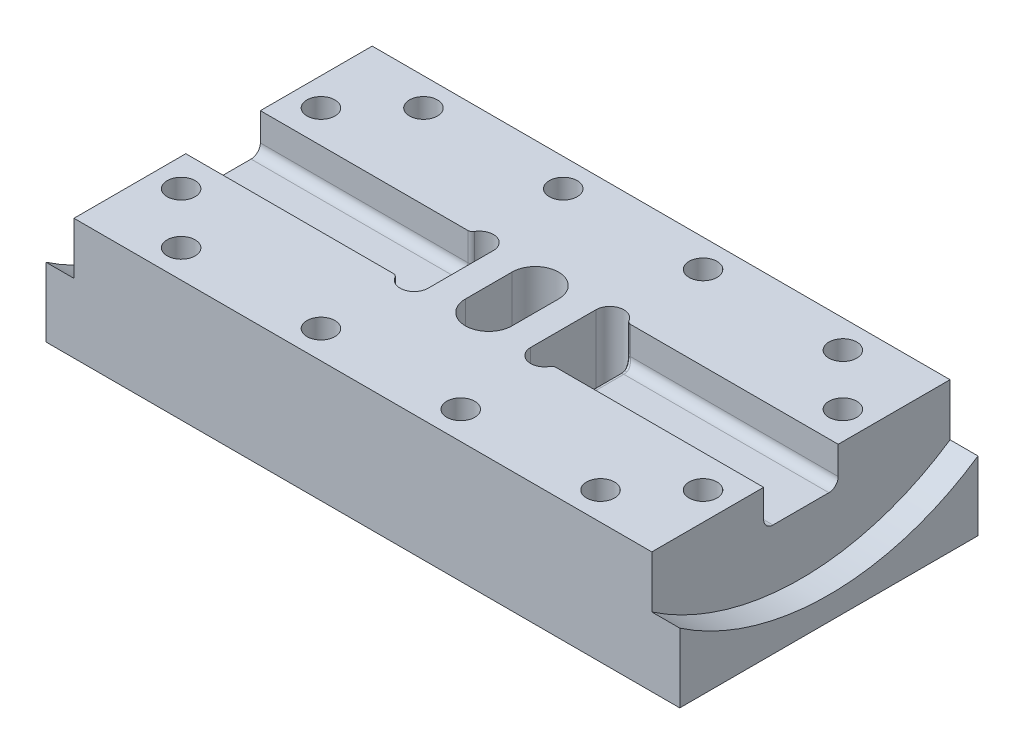
SolidWorks part; units mm, degrees
ref_plane "Front Plane" through (0, 0, 0) normal (0, 0, 1) x (1, 0, 0)
ref_plane "Top Plane" through (0, 0, 0) normal (0, 1, 0) x (1, 0, 0)
ref_plane "Right Plane" through (0, 0, 0) normal (1, 0, 0) x (0, 0, -1)
sketch "Sketch1" plane through (0, 0, 0) normal (0, 1, 0) x (1, 0, 0)
  line L1 (34, -16) -> (-34, -16)
  line L2 (34, -16) -> (34, 16)
  line L3 (34, 16) -> (-34, 16)
  line L4 (-34, -16) -> (-34, 16)
  line L5 (34, -16) -> (-34, 16) construction
  line L6 (34, 16) -> (-34, -16) construction
  point P0 (0, 0)
  dimension "D1" = 32
  dimension "D2" = 68
extrude "Boss-Extrude1" add sketch "Sketch1" along normal blind 13
sketch "Sketch2" plane through (0, 13, 0) normal (0, 1, 0) x (1, 0, 0)
  line L0 (-34, 16) -> (-34, -16) construction
  line L1 (28, -7.5) -> (-28, -7.5) construction
  line L2 (28, -7.5) -> (28, 7.5) construction
  line L3 (28, 7.5) -> (-28, 7.5) construction
  line L4 (-28, -7.5) -> (-28, 7.5) construction
  line L5 (28, -7.5) -> (-28, 7.5) construction
  line L6 (28, 7.5) -> (-28, -7.5) construction
  line L7 (-34, -16) -> (34, -16) construction
  line L8 (22.5, -13) -> (-22.5, -13) construction
  line L9 (22.5, -13) -> (22.5, 13) construction
  line L10 (22.5, 13) -> (-22.5, 13) construction
  line L11 (-22.5, -13) -> (-22.5, 13) construction
  line L12 (22.5, -13) -> (-22.5, 13) construction
  line L13 (22.5, 13) -> (-22.5, -13) construction
  line L14 (0, 0) -> (22.5, 0) construction
  circle A0 centre (-28, 7.5) radius 1.5
  circle A1 centre (-28, -7.5) radius 1.5
  circle A2 centre (28, -7.5) radius 1.5
  circle A3 centre (28, 7.5) radius 1.5
  circle A4 centre (-22.5, 13) radius 1.5
  circle A5 centre (-7.5, 13) radius 1.5
  circle A6 centre (7.5, 13) radius 1.5
  circle A7 centre (22.5, 13) radius 1.5
  circle A8 centre (-22.5, -13) radius 1.5
  circle A9 centre (-7.5, -13) radius 1.5
  circle A10 centre (7.5, -13) radius 1.5
  circle A11 centre (22.5, -13) radius 1.5
  point P0 (0, 0)
  point P12 (0, 0)
  dimension "D3" = 3
  dimension "D4" = 3
  dimension "D5" = 3
  dimension "D6" = 3
  dimension "D9" = 3
  dimension "D11" = 3
  dimension "D13" = 3
  dimension "D15" = 3
  dimension "D1" = 7.5
  dimension "D2" = 6
  dimension "D7" = 11.5
  dimension "D8" = 3
  dimension "D10" = 15
  dimension "D12" = 15
  dimension "D14" = 15
extrude "Cut-Extrude1" cut sketch "Sketch2" against normal through all
sketch "Sketch3" plane through (0, 13, 0) normal (0, 1, 0) x (1, 0, 0)
  line L0 (0, -2.5) -> (0, 2.5) construction
  line L1 (-2.5, -2.5) -> (-2.5, 2.5)
  line L2 (2.5, -2.5) -> (2.5, 2.5)
  line L3 (-7, -3.5) -> (-7, 3.5) construction
  line L4 (-8.5, -3.5) -> (-8.5, 3.5)
  line L5 (-5.5, -3.5) -> (-5.5, 3.5)
  line L6 (0, 0) -> (0, -16) construction
  line L9 (-34, -16) -> (34, -16) construction
  line L10 (7, -3.5) -> (7, 3.5) construction
  line L11 (8.5, -3.5) -> (8.5, 3.5)
  line L12 (5.5, -3.5) -> (5.5, 3.5)
  arc A0 (-2.5, -2.5) -> (2.5, -2.5) centre (0, -2.5) ccw
  arc A1 (2.5, 2.5) -> (-2.5, 2.5) centre (0, 2.5) ccw
  arc A2 (-8.5, -3.5) -> (-5.5, -3.5) centre (-7, -3.5) ccw
  arc A3 (-5.5, 3.5) -> (-8.5, 3.5) centre (-7, 3.5) ccw
  arc A6 (8.5, -3.5) -> (5.5, -3.5) centre (7, -3.5) cw
  arc A7 (5.5, 3.5) -> (8.5, 3.5) centre (7, 3.5) cw
  point P2 (0, 0)
  point P9 (-7, 0)
  point P21 (7, 0)
  point P22 (-2.5, 0)
  dimension "D2" = 10
  dimension "D5" = 10
  dimension "D1" = 5
  dimension "D3" = 3
  dimension "D4" = 3
extrude "Cut-Extrude2" cut sketch "Sketch3" against normal through all
sketch "Sketch5" plane through (0, 0, 0) normal (1, 0, 0) x (0, 0, -1)
  line L0 (-16, 13) -> (16, 13) construction
  line L5 (-16, 0) -> (16, 0)
  line L6 (16, 0) -> (16, 13)
  line L7 (16, 13) -> (-16, 13)
  line L8 (-16, 13) -> (-16, 0)
  line L10 (16, 7.415) -> (16, 13)
  line L11 (16, 13) -> (-16, 13)
  line L12 (-16, 13) -> (-16, 7.415)
  arc A0 (-16, 7.415) -> (16, 7.415) centre (0, 31) ccw
  dimension "D2" = 57
  dimension "D1" = 18
  dimension "D3" = 0
extrude "Cut-Extrude3" cut sketch "Sketch5" along normal blind 3 from surface at -34 starting at face at (-34, 6.5, 0)
sketch "Sketch6" plane through (0, 0, 0) normal (1, 0, 0) x (0, 0, -1)
  line L3 (16, 7.415) -> (16, 13)
  line L4 (16, 13) -> (-16, 13)
  line L5 (-16, 13) -> (-16, 7.415)
  line L6 (16, 7.415) -> (16, 13)
  line L7 (16, 13) -> (-16, 13)
  line L8 (-16, 13) -> (-16, 7.415)
  arc A1 (-16, 7.415) -> (16, 7.415) centre (0, 31) ccw
  arc A2 (-16, 7.415) -> (16, 7.415) centre (0, 31) ccw
  dimension "D1" = 0
extrude "Cut-Extrude4" cut sketch "Sketch6" against normal blind 3 from surface at 34 starting at face at (34, 6.5, 0)
sketch "Sketch7" plane through (-31, 0, 0) normal (-1, 0, 0) x (0, 0, 1)
  line L0 (-16, 13) -> (16, 13) construction
  line L1 (-4, 13) -> (4, 13)
  line L2 (-4, 13) -> (-4, 10)
  line L3 (-3, 9) -> (3, 9)
  line L4 (4, 13) -> (4, 10)
  arc A0 (3, 9) -> (4, 10) centre (3, 10) ccw
  arc A1 (-4, 10) -> (-3, 9) centre (-3, 10) ccw
  point P6 (0, 9)
  point P12 (-4, 9)
  dimension "D3" = 1
  dimension "D1" = 4
  dimension "D2" = 4
extrude "Cut-Extrude5" cut sketch "Sketch7" against normal blind 23
sketch "Sketch8" plane through (31, 0, 0) normal (1, 0, 0) x (0, 0, -1)
  line L4 (4, 13) -> (-4, 13)
  line L5 (-4, 13) -> (-4, 10)
  line L6 (-3, 9) -> (3, 9)
  line L7 (4, 10) -> (4, 13)
  line L8 (4, 13) -> (-4, 13)
  line L9 (-4, 13) -> (-4, 10)
  line L10 (-3, 9) -> (3, 9)
  line L11 (4, 10) -> (4, 13)
  arc A2 (-4, 10) -> (-3, 9) centre (-3, 10) ccw
  arc A3 (3, 9) -> (4, 10) centre (3, 10) ccw
  arc A4 (-4, 10) -> (-3, 9) centre (-3, 10) ccw
  arc A5 (3, 9) -> (4, 10) centre (3, 10) ccw
  dimension "D1" = 0
extrude "Cut-Extrude6" cut sketch "Sketch8" against normal blind 23
fillet "Fillet1" radius 0.5 14 edges at (8.4142, 11.5, 4) (8.4712, 9.3902, 3.7925) (8.5, 9.0341, 3.2588) (8.4142, 11.5, -4) (8.4389, 9.6172, -3.9238) (8.5, 9.0341, -3.2588) (-8.4142, 11.5, -4) (-8.4712, 9.3902, -3.7925) (-8.5, 9.0341, -3.2588) (-8.5, 9, 0) (-8.5, 9.0341, 3.2588) (-8.4389, 9.6172, 3.9238) (8.5, 9, 0) (-8.4142, 11.5, 4)
